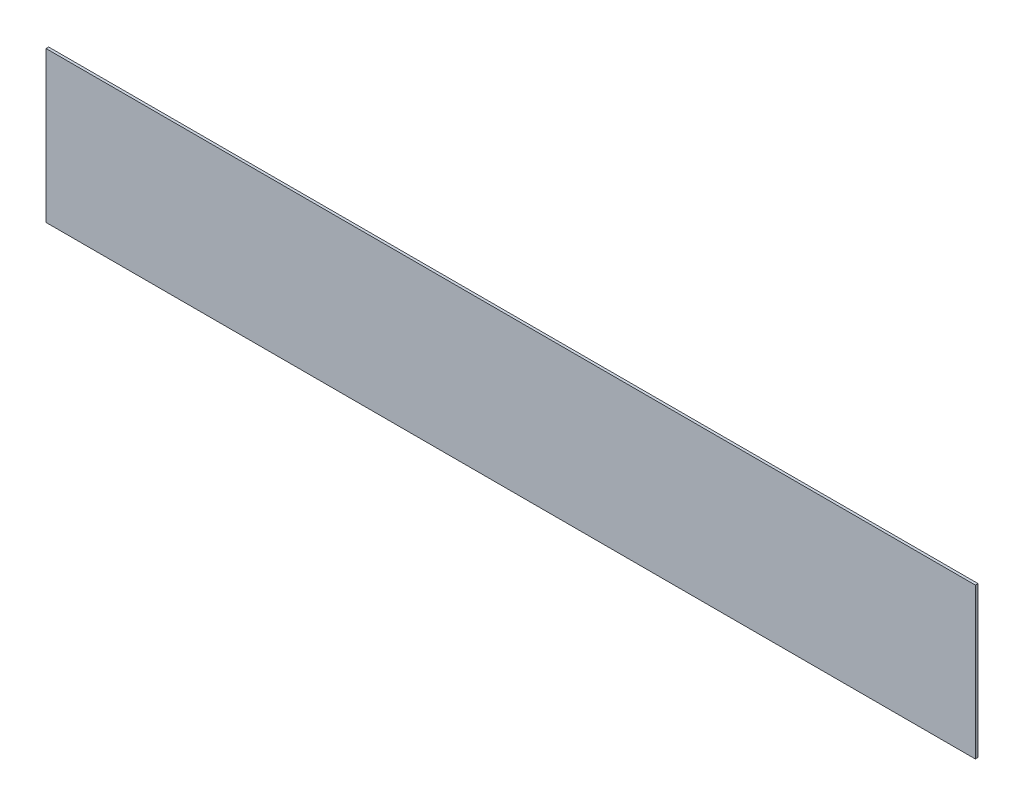
SolidWorks part; units mm, degrees
ref_plane "Front Plane" through (0, 0, 0) normal (0, 0, 1) x (1, 0, 0)
ref_plane "Top Plane" through (0, 0, 0) normal (0, 1, 0) x (1, 0, 0)
ref_plane "Right Plane" through (0, 0, 0) normal (1, 0, 0) x (0, 0, -1)
sketch "Sketch1" plane through (0, 0, 0) normal (0, 0, 1) x (1, 0, 0)
  line L1 (0, 0) -> (447, 0)
  line L2 (0, 0) -> (0, 72.46)
  line L3 (0, 72.46) -> (447, 72.46)
  line L4 (447, 0) -> (447, 72.46)
  dimension "D1" = 72.46
  dimension "D2" = 447
extrude "Boss-Extrude1" add sketch "Sketch1" along normal blind 1.27
